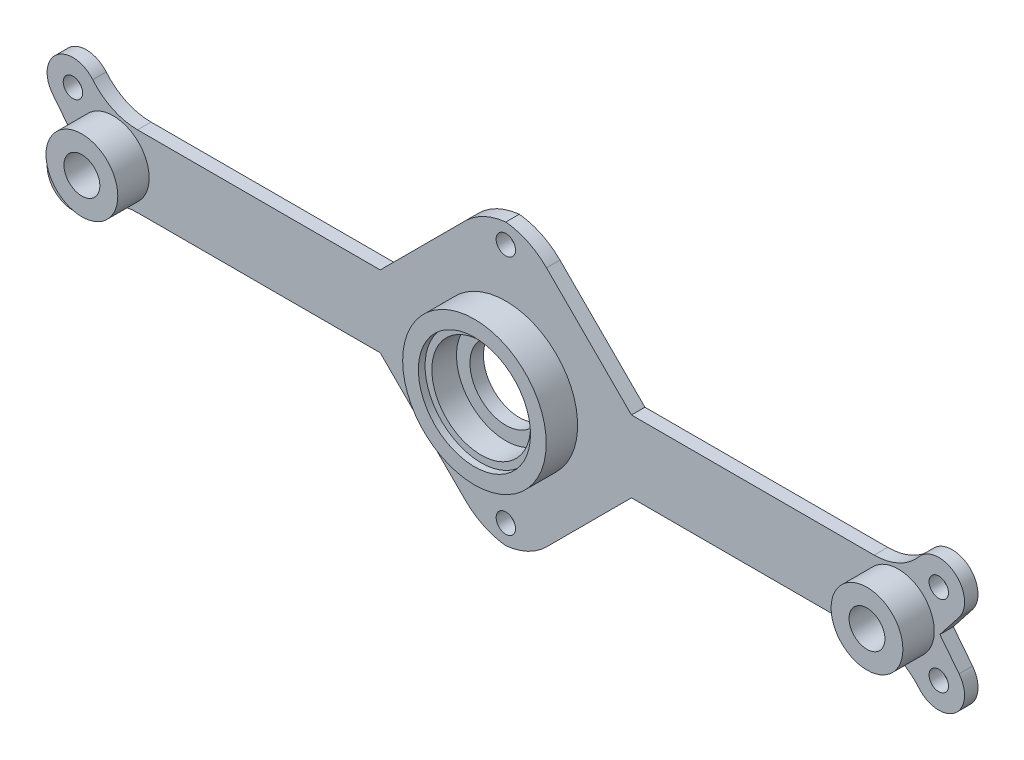
SolidWorks part; units mm, degrees
ref_plane "Front" through (0, 0, 0) normal (0, 0, 1) x (1, 0, 0)
ref_plane "Top" through (0, 0, 0) normal (0, 1, 0) x (1, 0, 0)
ref_plane "Right" through (0, 0, 0) normal (1, 0, 0) x (0, 0, -1)
sketch "Sketch1" plane through (0, 0, 0) normal (0, 0, 1) x (1, 0, 0)
  line L1 (-102.25, -31.25) -> (102.25, -31.25)
  line L2 (-102.25, -31.25) -> (-102.25, 31.25)
  line L3 (-102.25, 31.25) -> (102.25, 31.25)
  line L4 (102.25, -31.25) -> (102.25, 31.25)
  line L5 (-102.25, -31.25) -> (102.25, 31.25) construction
  line L6 (-102.25, 31.25) -> (102.25, -31.25) construction
  point P0 (0, 0)
  dimension "D1" = 204.5
  dimension "D2" = 62.5
extrude "Boss-Extrude1" add sketch "Sketch1" along normal blind 3
sketch "Sketch2" plane through (0, 0, 3) normal (0, 0, 1) x (1, 0, 0)
  line L0 (-87.5, 0) -> (87.5, 0) construction
  circle A0 centre (-87.5, 0) radius 8
  circle A1 centre (87.5, 0) radius 8
  point P4 (0, 0)
  dimension "D2" = 16
  dimension "D1" = 175
extrude "Boss-Extrude2" add sketch "Sketch2" along normal blind 7
sketch "Sketch3" plane through (0, 0, 3) normal (0, 0, 1) x (1, 0, 0)
  circle A0 centre (0, 0) radius 16
  dimension "D1" = 32
extrude "Boss-Extrude3" add sketch "Sketch3" along normal blind 7
sketch "Sketch4" plane through (0, 0, 3) normal (0, 0, 1) x (1, 0, 0)
  line L0 (-96.5, 9) -> (-96.5, -9) construction
  circle A0 centre (-96.5, 9) radius 2.165
  circle A1 centre (-96.5, -9) radius 2.165
  point P2 (-96.5, 0)
  dimension "D2" = 4.33
  dimension "D1" = 96.5
  dimension "D3" = 18
extrude "Cut-Extrude1" cut sketch "Sketch4" against normal through all
sketch "Sketch5" plane through (0, 0, 3) normal (0, 0, 1) x (1, 0, 0)
  line L0 (0, 26.875) -> (0, -26.875) construction
  circle A0 centre (0, 26.875) radius 2.165
  circle A1 centre (0, -26.875) radius 2.165
  point P3 (0, 0)
  dimension "D2" = 4.33
  dimension "D1" = 53.75
extrude "Cut-Extrude2" cut sketch "Sketch5" against normal through all
sketch "Sketch6" plane through (0, 0, 3) normal (0, 0, 1) x (1, 0, 0)
  line L0 (-82.093, -8) -> (-28, -8)
  line L1 (-28, -8) -> (-9.0639, -26.9361)
  line L2 (0, -31.25) -> (0, 0) construction
  line L3 (-102.25, -31.25) -> (102.25, -31.25) construction
  line L4 (-102.25, 31.25) -> (-102.25, -31.25) construction
  line L5 (0, -31.25) -> (-102.25, -31.25)
  line L6 (-102.25, -31.25) -> (-102.25, -9)
  line L7 (-102.25, 0) -> (-96.75, 0)
  line L8 (-96.75, 0) -> (-101.0249, -5.4521)
  line L9 (-102.25, 0) -> (-102.25, -9)
  arc A0 (0, -31.25) -> (-9.0639, -26.9361) centre (1.5428, -16.3295) cw
  arc A1 (-101.0249, -5.4521) -> (-92.0818, -12.68) centre (-96.5, -9) ccw
  arc A3 (-82.093, -8) -> (-92.0818, -12.68) centre (-82.093, -21) ccw
  line M8 (-102.25, 31.25) -> (-102.25, -31.25)
  line M9 (-102.25, -31.25) -> (102.25, -31.25)
  dimension "D4" = 15
  dimension "D5" = 13
  dimension "D1" = 45
  dimension "D2" = 8
  dimension "D3" = 28
  dimension "D6" = 5.5
extrude "Cut-Extrude3" cut sketch "Sketch6" against normal blind 7 contours A1 L8 L7 M8 | L0 A3 A1 A0 L1 M8 M9
mirror "Mirror1" about plane through (0, 0, 0) normal (1, 0, 0) of "Cut-Extrude1", "Cut-Extrude3"
mirror "Mirror2" about plane through (0, 0, 0) normal (0, 1, 0) of "Mirror1", "Cut-Extrude3"
sketch "Sketch7" plane through (0, 0, 10) normal (0, 0, 1) x (1, 0, 0)
  circle A0 centre (0, 0) radius 12.5
  dimension "D1" = 25
extrude "Cut-Extrude4" cut sketch "Sketch7" against normal blind 1.5
sketch "Sketch9" plane through (0, 0, 10) normal (0, 0, 1) x (1, 0, 0)
  circle A0 centre (0, 0) radius 11
  dimension "D1" = 22
extrude "Cut-Extrude5" cut sketch "Sketch9" against normal blind 7
sketch "Sketch10" plane through (0, 0, 3) normal (0, 0, 1) x (1, 0, 0)
  circle A0 centre (0, 0) radius 8
  dimension "D1" = 16
extrude "Cut-Extrude6" cut sketch "Sketch10" against normal through all
sketch "Sketch11" plane through (0, 0, 10) normal (0, 0, 1) x (1, 0, 0)
  circle A0 centre (-87.5, 0) radius 4
  circle A1 centre (87.5, 0) radius 4
  dimension "D1" = 8
extrude "Cut-Extrude7" cut sketch "Sketch11" against normal blind 7
